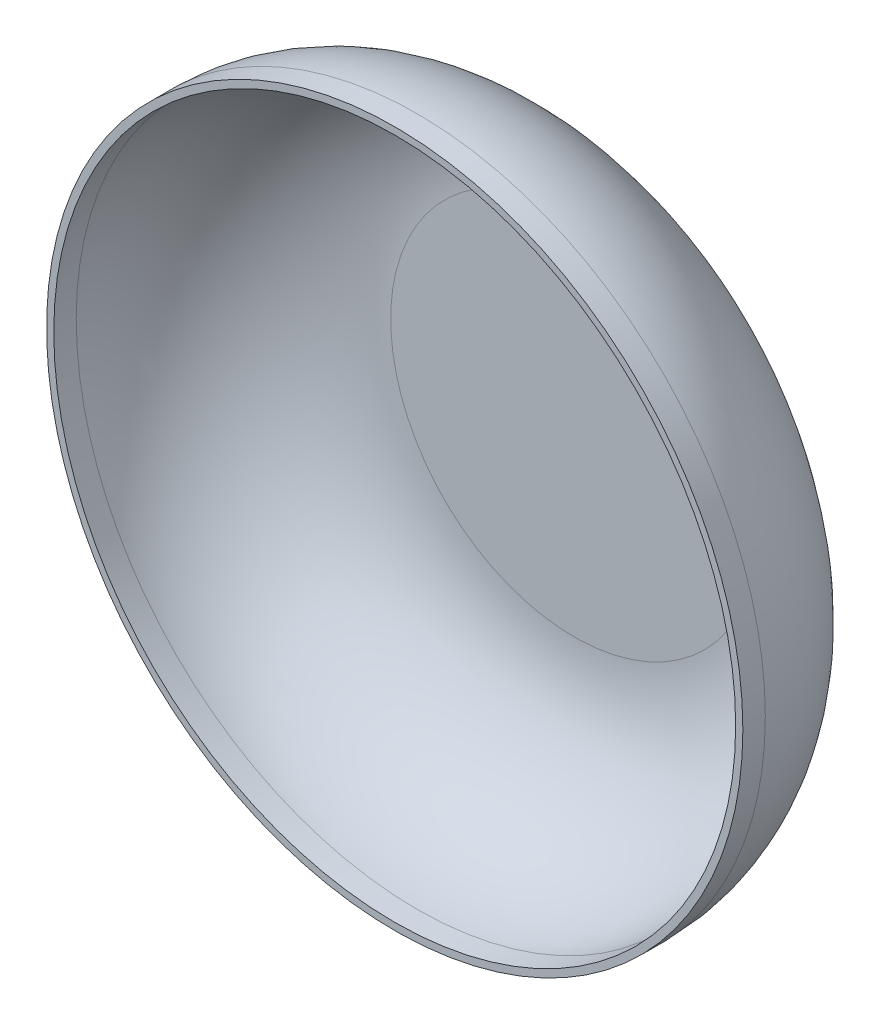
SolidWorks part; units mm, degrees
ref_plane "Front Plane" through (0, 0, 0) normal (0, 0, 1) x (1, 0, 0)
ref_plane "Top Plane" through (0, 0, 0) normal (0, 1, 0) x (1, 0, 0)
ref_plane "Right Plane" through (0, 0, 0) normal (1, 0, 0) x (0, 0, -1)
sketch "Sketch1" plane through (0, 0, 0) normal (0, 1, 0) x (1, 0, 0)
  line L0 (0, 0) -> (0, 416) construction
  line L1 (0, 0) -> (759, 0) construction
  line L2 (759, 0) -> (759, 50)
  line L3 (759, 50) -> (409, 50) construction
  line L4 (0, 0) -> (775, 0) construction
  line L5 (409, 400) -> (0, 400)
  line L6 (0, 400) -> (0, 416)
  line L7 (759, 0) -> (775, 0)
  line L8 (0, 416) -> (409, 416)
  line L9 (775, 0) -> (775, 50)
  arc A0 (759, 50) -> (409, 400) centre (409, 50) ccw
  arc A1 (775, 50) -> (409, 416) centre (409, 50) ccw
  dimension "D6" = 366
  dimension "D1" = 416
  dimension "D2" = 759
  dimension "D3" = 50
  dimension "D4" = 350
  dimension "D5" = 775
revolve "Revolve1" add sketch "Sketch1" angle 360 about L0
